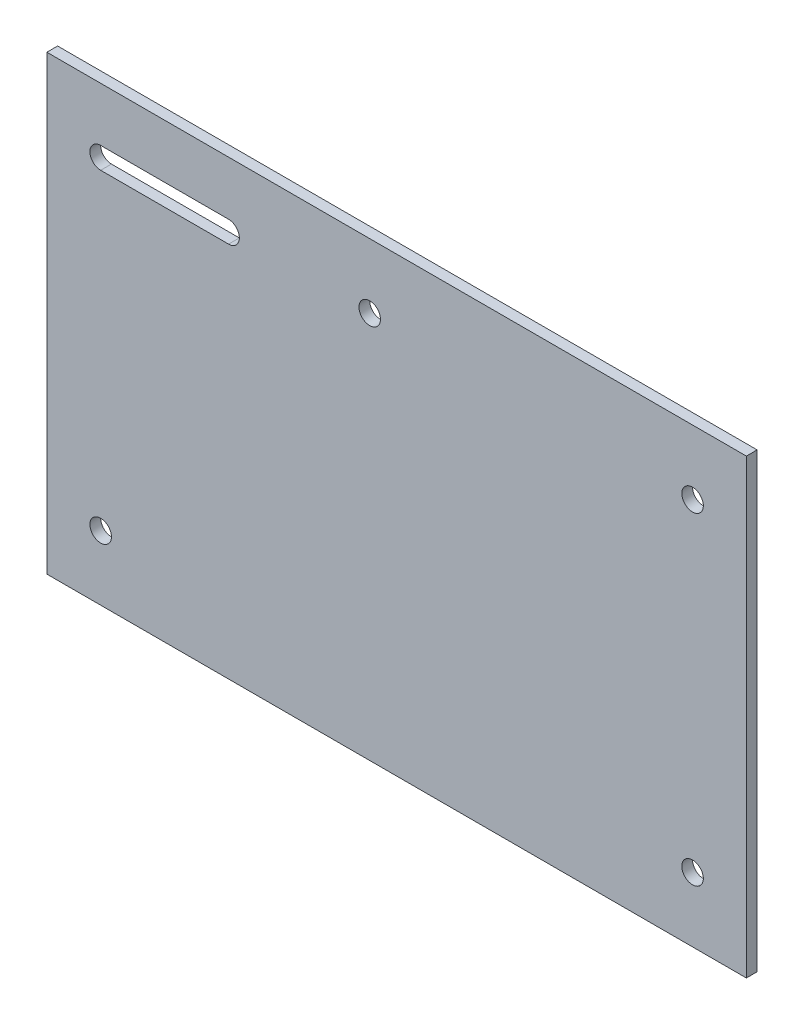
SolidWorks part; units mm, degrees
ref_plane "Front Plane" through (0, 0, 0) normal (0, 0, 1) x (1, 0, 0)
ref_plane "Top Plane" through (0, 0, 0) normal (0, 1, 0) x (1, 0, 0)
ref_plane "Right Plane" through (0, 0, 0) normal (1, 0, 0) x (0, 0, -1)
sketch "Sketch1" plane through (0, 0, 0) normal (0, 0, 1) x (1, 0, 0)
  line L1 (-65, -42) -> (65, -42)
  line L2 (-65, -42) -> (-65, 42)
  line L3 (-65, 42) -> (65, 42)
  line L4 (65, -42) -> (65, 42)
  line L5 (-65, -42) -> (65, 42) construction
  line L6 (-65, 42) -> (65, -42) construction
  point P0 (0, 0)
  dimension "D1" = 130
  dimension "D2" = 84
extrude "Boss-Extrude1" add sketch "Sketch1" along normal blind 2
sketch "Sketch2" plane through (0, 0, 2) normal (0, 0, 1) x (1, 0, 0)
  line L0 (65, -42) -> (65, 42) construction
  line L1 (65, 42) -> (-65, 42) construction
  line L2 (-65, 42) -> (-65, -42) construction
  line L3 (-65, -42) -> (65, -42) construction
  circle A0 centre (55, -30) radius 2
  circle A1 centre (-55, -30) radius 2
  circle A2 centre (55, 30) radius 2
  circle A3 centre (-5, 30) radius 2
  dimension "D1" = 4
  dimension "D2" = 4
  dimension "D3" = 4
  dimension "D4" = 4
  dimension "D5" = 10
  dimension "D6" = 12
  dimension "D7" = 12
  dimension "D8" = 70
  dimension "D9" = 10
  dimension "D10" = 10
  dimension "D12" = 12
  dimension "D11" = 12
extrude "Cut-Extrude1" cut sketch "Sketch2" against normal blind 2
sketch "Sketch3" plane through (0, 0, 2) normal (0, 0, 1) x (1, 0, 0)
  line L0 (-55, 30) -> (-31.2299, 30) construction
  line L1 (-55, 32) -> (-31.2299, 32)
  line L2 (-55, 28) -> (-31.2299, 28)
  line L3 (-65, 42) -> (-65, -42) construction
  line L4 (65, 42) -> (-65, 42) construction
  arc A0 (-55, 32) -> (-55, 28) centre (-55, 30) ccw
  arc A1 (-31.2299, 28) -> (-31.2299, 32) centre (-31.2299, 30) ccw
  point P2 (-43.1149, 30)
  dimension "D1" = 2
  dimension "D2" = 10
  dimension "D3" = 12
extrude "Cut-Extrude2" cut sketch "Sketch3" against normal blind 2
